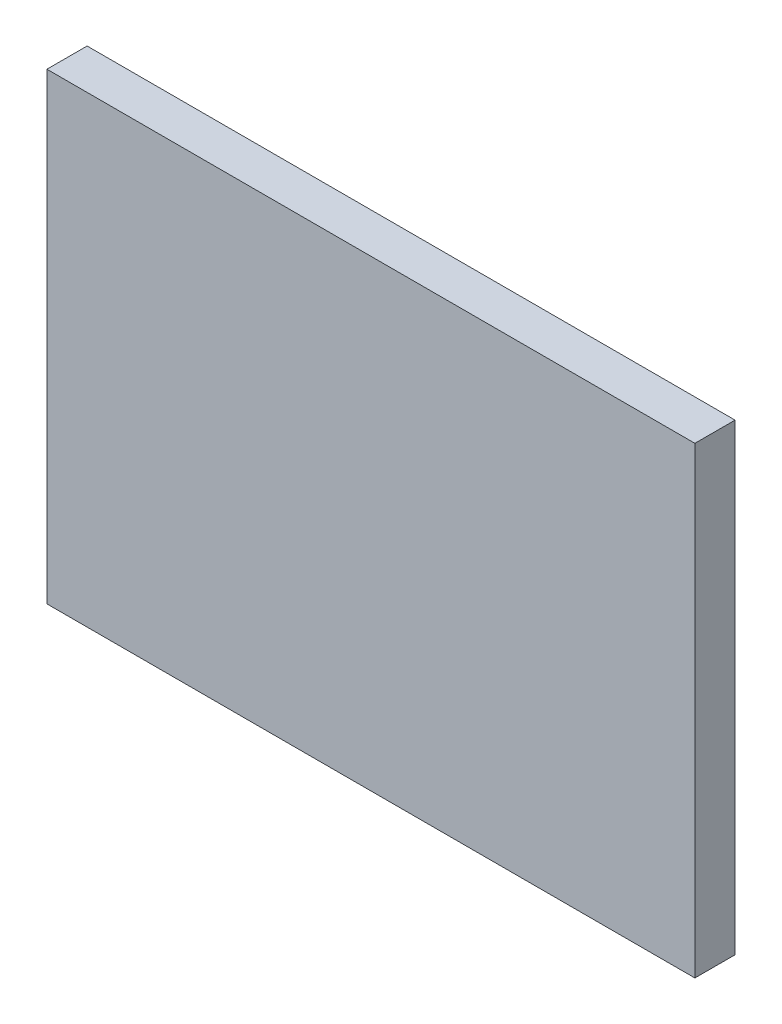
SolidWorks part; units mm, degrees
ref_plane "Plano frontal" through (0, 0, 0) normal (0, 0, 1) x (1, 0, 0)
ref_plane "Plano superior" through (0, 0, 0) normal (0, 1, 0) x (1, 0, 0)
ref_plane "Plano direito" through (0, 0, 0) normal (1, 0, 0) x (0, 0, -1)
sketch "Esboço1" plane through (0, 0, 0) normal (0, 0, 1) x (1, 0, 0)
  line L1 (201.5, -144) -> (-201.5, -144)
  line L2 (201.5, -144) -> (201.5, 144)
  line L3 (201.5, 144) -> (-201.5, 144)
  line L4 (-201.5, -144) -> (-201.5, 144)
  line L5 (201.5, -144) -> (-201.5, 144) construction
  line L6 (201.5, 144) -> (-201.5, -144) construction
  point P0 (0, 0)
  dimension "D1" = 288
  dimension "D2" = 403
extrude "Ressalto-extrusão1" add sketch "Esboço1" along normal blind 25
sketch "Esboço2" plane through (0, 0, 0) normal (0, 0, -1) x (-1, 0, 0)
  text T0 "17,3'" font "Century Gothic" height in points 80
  point P1 (-129.0059, 78.9026)
  point P2 (-61.1904, 19.0136)
  point P3 (-25.9616, 0)
extrude "Corte-extrusão1" cut sketch "Esboço2" against normal blind 10
